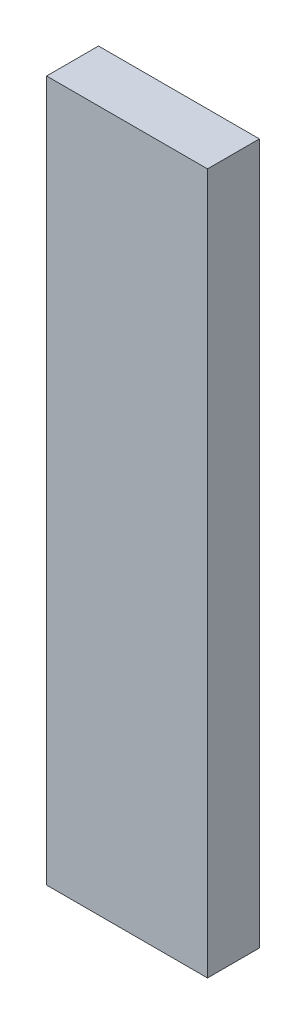
SolidWorks part; units mm, degrees
ref_plane "Front Plane" through (0, 0, 0) normal (0, 0, 1) x (1, 0, 0)
ref_plane "Top Plane" through (0, 0, 0) normal (0, 1, 0) x (1, 0, 0)
ref_plane "Right Plane" through (0, 0, 0) normal (1, 0, 0) x (0, 0, -1)
sketch "Sketch1" plane through (0, 0, 0) normal (0, 1, 0) x (1, 0, 0)
  line L1 (-33.0667, -32.6238) -> (28.9333, -32.6238)
  line L2 (-33.0667, -32.6238) -> (-33.0667, -12.6238)
  line L3 (-33.0667, -12.6238) -> (28.9333, -12.6238)
  line L4 (28.9333, -32.6238) -> (28.9333, -12.6238)
  point P4 (0, 0)
  point P5 (0, 0)
  point P6 (0, 0)
  dimension "D1" = 62
  dimension "D2" = 20
extrude "Boss-Extrude1" add sketch "Sketch1" along normal blind 270
shell "Shell1" thickness 1.2
